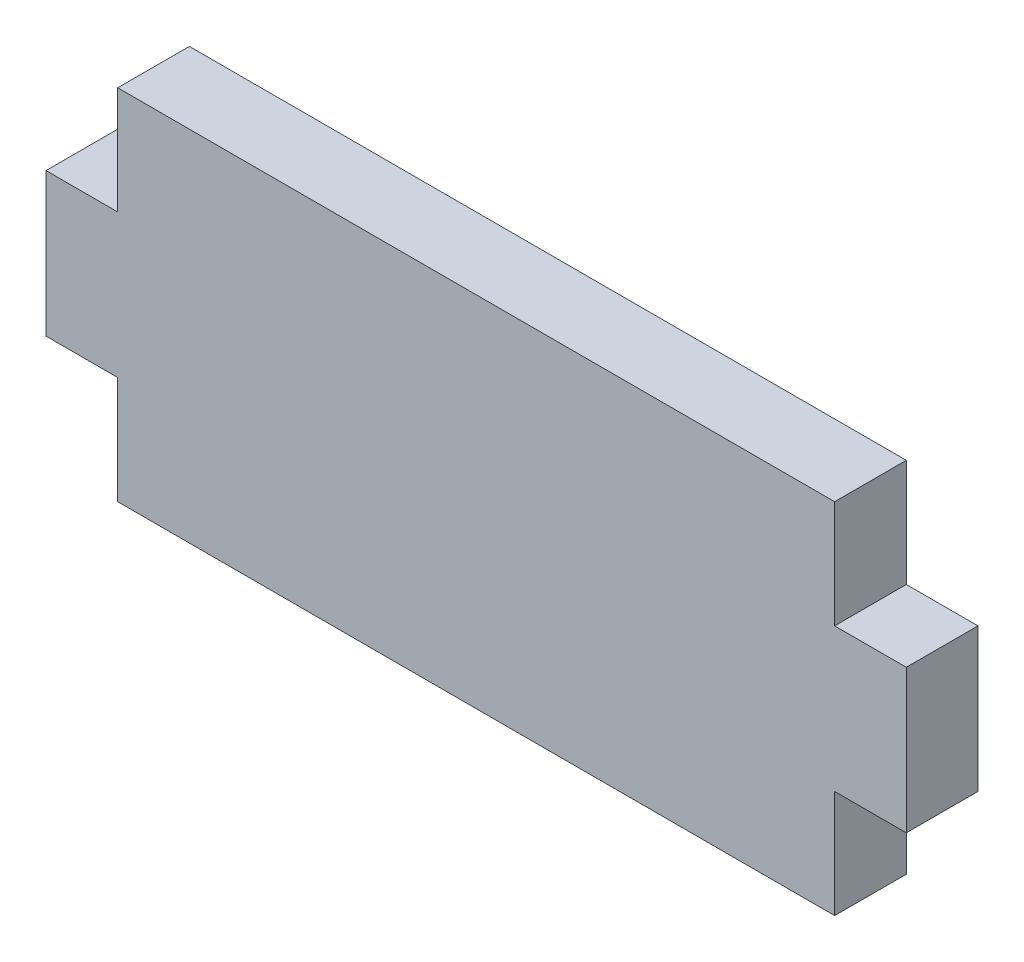
SolidWorks part; units mm, degrees
ref_plane "Plan de face" through (0, 0, 0) normal (0, 0, 1) x (1, 0, 0)
ref_plane "Plan de dessus" through (0, 0, 0) normal (0, 1, 0) x (1, 0, 0)
ref_plane "Plan de droite" through (0, 0, 0) normal (1, 0, 0) x (0, 0, -1)
sketch "Esquisse1" plane through (0, 0, 0) normal (0, 0, 1) x (1, 0, 0)
  line L1 (0, 0) -> (100, 0)
  line L2 (0, 0) -> (0, 50)
  line L3 (0, 50) -> (100, 50)
  line L4 (100, 0) -> (100, 50)
  line L5 (0, 35) -> (-10, 35)
  line L6 (0, 35) -> (0, 15)
  line L7 (0, 15) -> (-10, 15)
  line L8 (-10, 35) -> (-10, 15)
  line L9 (100, 35) -> (110, 35)
  line L10 (100, 35) -> (100, 15)
  line L11 (100, 15) -> (110, 15)
  line L12 (110, 35) -> (110, 15)
  point P13 (-10, 25)
  point P14 (0, 25)
  point P15 (110, 25)
  point P16 (100, 25)
  dimension "D1" = 100
  dimension "D2" = 50
  dimension "D3" = 10
  dimension "D4" = 20
  dimension "D5" = 10
  dimension "D6" = 20
extrude "Boss.-Extru.1" add sketch "Esquisse1" along normal blind 10 contours L5 L8 L7 L2 | L1 L4 L3 L2 | L12 L9 L4 L11
